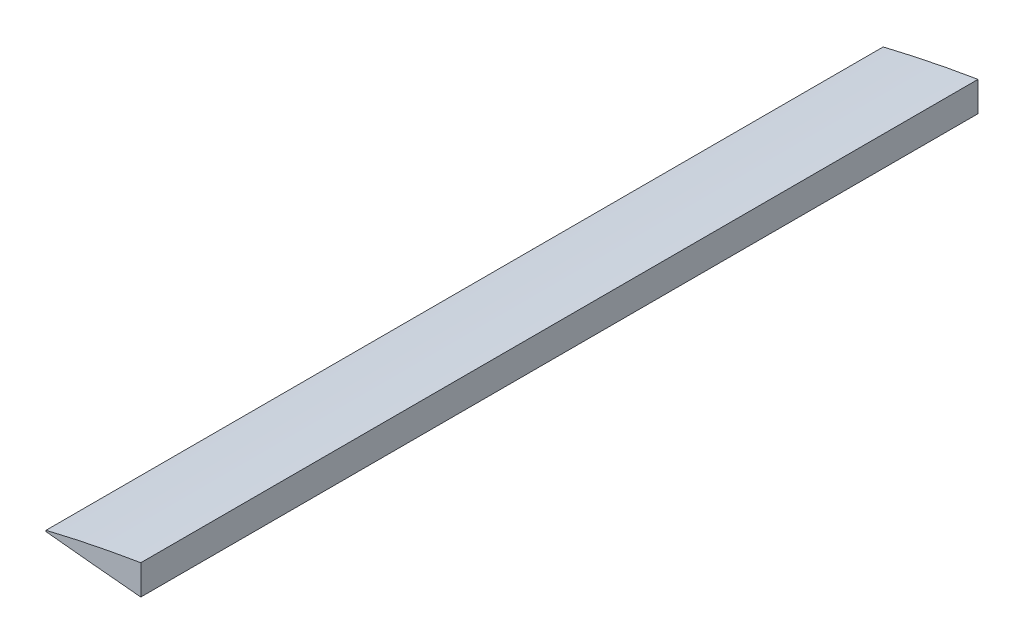
SolidWorks part; units mm, degrees
ref_plane "Front Plane" through (0, 0, 0) normal (0, 0, 1) x (1, 0, 0)
ref_plane "Top Plane" through (0, 0, 0) normal (0, 1, 0) x (1, 0, 0)
ref_plane "Right Plane" through (0, 0, 0) normal (1, 0, 0) x (0, 0, -1)
sketch "Sketch1" plane through (0, 0, 0) normal (0, 0, 1) x (1, 0, 0)
  line L0 (-197.267, 14.5456) -> (-197.267, -7.2089)
  line L1 (-266.577, 0.4257) -> (-266.577, -0.4189)
  spline S0 degree 3 poles (-197.267, 14.5456) (-199.2913, 14.2098) (-204.2167, 13.3929) (-211.8679, 12.0299) (-220.0467, 10.5109) (-227.685, 9.0242) (-234.7376, 7.5953) (-241.1628, 6.245) (-246.9227, 4.9942) (-251.9835, 3.8631) (-256.316, 2.8703) (-259.895, 2.0327) (-262.7001, 1.365) (-264.7152, 0.8792) (-265.9195, 0.5864) (-266.4509, 0.4566) (-266.577, 0.4257) knots 0 0 0 0 0.087007 0.211705 0.329527 0.439741 0.541661 0.634652 0.718135 0.791585 0.85454 0.906603 0.947445 0.976805 0.994497 1 1 1 1
  spline S1 degree 3 poles (-197.267, -7.2089) (-199.0197, -7.05) (-203.6784, -6.6277) (-211.0841, -5.9396) (-219.3093, -5.1648) (-227.0092, -4.427) (-234.1351, -3.7336) (-240.6411, -3.0907) (-246.4855, -2.5047) (-251.6304, -1.981) (-256.0423, -1.5274) (-259.6922, -1.1436) (-262.5569, -0.8499) (-264.6155, -0.6129) (-265.8584, -0.5128) (-266.419, -0.4184) (-266.5677, -0.4189) (-266.577, -0.4189) knots 0 0 0 0 0.075811 0.201508 0.320388 0.431695 0.534719 0.628797 0.713321 0.78774 0.851567 0.90438 0.945827 0.975633 0.993597 0.999599 1 1 1 1
extrude "Boss-Extrude1" add sketch "Sketch1" along normal blind 612
ref_plane "Plane1" through (0, 0, 83.9) normal (0, 0, 1) x (1, 0, 0)
sketch "Sketch2" plane through (0, 0, 83.9) normal (0, 0, 1) x (1, 0, 0)
  line L0 (-220.432, -7.777) -> (-199.432, -7.777)
  line L1 (-199.432, -7.777) -> (-199.432, 3.723)
  line L2 (-199.432, 3.723) -> (-220.432, 3.723)
  line L3 (-220.432, 3.723) -> (-220.432, -7.777)
extrude "Cut-Extrude1" cut sketch "Sketch2" along normal blind 13
